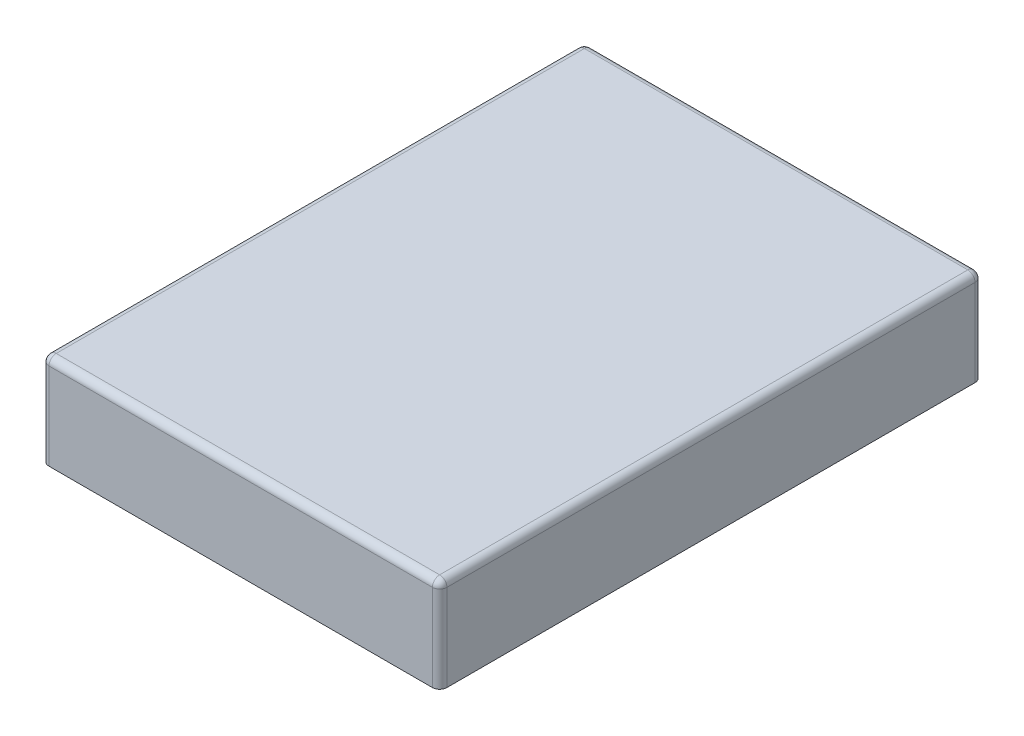
SolidWorks part; units mm, degrees
ref_plane "Front Plane" through (0, 0, 0) normal (0, 0, 1) x (1, 0, 0)
ref_plane "Top Plane" through (0, 0, 0) normal (0, 1, 0) x (1, 0, 0)
ref_plane "Right Plane" through (0, 0, 0) normal (1, 0, 0) x (0, 0, -1)
sketch "Sketch1" plane through (0, 0, 0) normal (0, 1, 0) x (1, 0, 0)
  line L1 (-27.5, -37.5) -> (27.5, -37.5)
  line L2 (-27.5, -37.5) -> (-27.5, 37.5)
  line L3 (-27.5, 37.5) -> (27.5, 37.5)
  line L4 (27.5, -37.5) -> (27.5, 37.5)
  line L5 (-27.5, -37.5) -> (27.5, 37.5) construction
  line L6 (-27.5, 37.5) -> (27.5, -37.5) construction
  point P0 (0, 0)
  dimension "D1" = 55
  dimension "D2" = 75
extrude "Boss-Extrude1" add sketch "Sketch1" along normal blind 13
fillet "Fillet1" radius 1 8 edges at (-27.5, 13, 0) (0, 13, -37.5) (0, 13, 37.5) (27.5, 13, 0) (-27.5, 6.5, 37.5) (-27.5, 6.5, -37.5) (27.5, 6.5, -37.5) (27.5, 6.5, 37.5)
